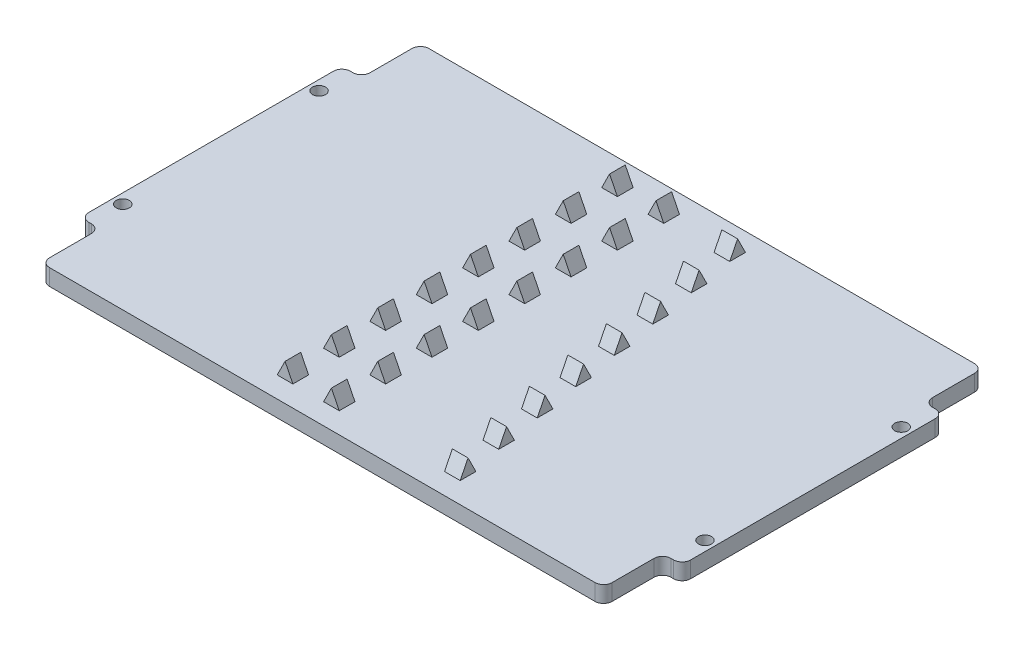
SolidWorks part; units mm, degrees
ref_plane "Front Plane" through (0, 0, 0) normal (0, 0, 1) x (1, 0, 0)
ref_plane "Top Plane" through (0, 0, 0) normal (0, 1, 0) x (1, 0, 0)
ref_plane "Right Plane" through (0, 0, 0) normal (1, 0, 0) x (0, 0, -1)
sketch "Sketch1" plane through (0, 0, 0) normal (0, 1, 0) x (1, 0, 0)
  line L1 (-54.61, -36.83) -> (54.61, -36.83)
  line L2 (-54.61, -36.83) -> (-54.61, 36.83)
  line L3 (-54.61, 36.83) -> (54.61, 36.83)
  line L4 (54.61, -36.83) -> (54.61, 36.83)
  line L5 (-54.61, -36.83) -> (54.61, 36.83) construction
  line L6 (-54.61, 36.83) -> (54.61, -36.83) construction
  point P0 (0, 0)
  dimension "D1" = 109.22
  dimension "D2" = 73.66
extrude "Boss-Extrude1" add sketch "Sketch1" against normal blind 3.175
ref_plane "Plane1" through (0, 0, -31.75) normal (0, 0, 1) x (1, 0, 0)
sketch "Sketch2" plane through (0, 0, -31.75) normal (0, 0, 1) x (1, 0, 0)
  line L0 (-12.81, 0) -> (-11.286, 3.048)
  line L3 (-11.286, 0) -> (-12.81, 0)
  line L4 (-11.286, 3.048) -> (-11.286, 0) construction
  line L5 (-11.286, 3.048) -> (-9.762, 0)
  line L6 (-54.61, 0) -> (54.61, 0) construction
  line L7 (-9.762, 0) -> (-11.286, 0)
  point P5 (-12.048, 0)
  dimension "D1" = 1.524
  dimension "D2" = 3.048
  dimension "D3" = 12.048
extrude "Boss-Extrude3" add sketch "Sketch2" along normal mid plane 3.048
pattern_linear "LPattern1" count 2 spacing 9 along (1, 0, 0) count 8 spacing 9 along (0, 0, 1) of "Boss-Extrude3"
sketch "Sketch3" plane through (0, 0, 0) normal (0, 1, 0) x (1, 0, 0)
  line L0 (-54.61, 36.83) -> (-54.61, -36.83) construction
  line L1 (-54.61, 25.4) -> (-58.42, 25.4)
  line L2 (-54.61, 25.4) -> (-54.61, -25.4)
  line L3 (-54.61, -25.4) -> (-58.42, -25.4)
  line L4 (-58.42, 25.4) -> (-58.42, -25.4)
  line L5 (0, 0) -> (0, 36.83) construction
  line L6 (54.61, 36.83) -> (-54.61, 36.83) construction
  line L7 (58.42, 25.4) -> (58.42, -25.4)
  line L8 (54.61, -25.4) -> (58.42, -25.4)
  line L9 (54.61, 25.4) -> (54.61, -25.4)
  line L10 (54.61, 25.4) -> (58.42, 25.4)
  circle A0 centre (-56.515, 19.05) radius 1.27
  circle A1 centre (-56.515, -19.05) radius 1.27
  circle A2 centre (56.515, -19.05) radius 1.27
  circle A3 centre (56.515, 19.05) radius 1.27
  point P6 (-58.42, 0)
  point P11 (-56.515, 25.4)
  dimension "D3" = 2.54
  dimension "D1" = 3.81
  dimension "D2" = 50.8
  dimension "D4" = 19.05
  dimension "D5" = 2
extrude "Boss-Extrude2" add sketch "Sketch3" against normal blind 3.175
fillet "Fillet1" radius 1.651 12 edges at (54.61, -1.5875, -36.83) (54.61, -1.5875, -25.4) (58.42, -1.5875, -25.4) (58.42, -1.5875, 25.4) (54.61, -1.5875, 25.4) (54.61, -1.5875, 36.83) (-54.61, -1.5875, 36.83) (-54.61, -1.5875, 25.4) (-58.42, -1.5875, 25.4) (-58.42, -1.5875, -25.4) (-54.61, -1.5875, -25.4) (-54.61, -1.5875, -36.83)
sketch "Sketch4" plane through (0, 0, 0) normal (1, 0, 0) x (0, 0, -1)
  line L0 (30.226, 0) -> (33.274, 0)
  line L1 (-23.749, 0) -> (23.749, 0) construction
  line L2 (33.274, 0) -> (31.75, 3.048)
  line L3 (31.75, 3.048) -> (30.226, 0)
  line L4 (31.75, 3.048) -> (31.75, 0) construction
  line L5 (12.226, 3.048) -> (15.274, 3.048) construction
  line L6 (30.226, 0) -> (33.274, 0) construction
extrude "Boss-Extrude4" add sketch "Sketch4" along normal blind 3.048 from offset 9
sketch "Sketch5" plane through (0, 0, 0) normal (1, 0, 0) x (0, 0, -1)
  line L0 (21.226, 0) -> (24.274, 0)
  line L2 (24.274, 0) -> (22.75, 3.048)
  line L3 (22.75, 3.048) -> (21.226, 0)
  line L4 (22.75, 3.048) -> (22.75, 0) construction
  line L7 (21.226, 0) -> (24.274, 0) construction
extrude "Boss-Extrude5" add sketch "Sketch5" along normal blind 3.048 from offset 10.524
sketch "Sketch6" plane through (0, 0, 0) normal (1, 0, 0) x (0, 0, -1)
  line L0 (12.226, 0) -> (15.274, 0)
  line L1 (12.226, 0) -> (15.274, 0) construction
  line L2 (15.274, 0) -> (13.75, 3.048)
  line L3 (13.75, 3.048) -> (12.226, 0)
  line L4 (13.75, 3.048) -> (13.75, 0) construction
extrude "Boss-Extrude6" add sketch "Sketch6" along normal blind 3.048 from offset 12.048
sketch "Sketch7" plane through (0, 0, 0) normal (1, 0, 0) x (0, 0, -1)
  line L0 (3.226, 0) -> (6.274, 0)
  line L2 (6.274, 0) -> (4.75, 3.048)
  line L3 (4.75, 3.048) -> (3.226, 0)
  line L4 (4.75, 3.048) -> (4.75, 0) construction
  line L5 (3.226, 0) -> (6.274, 0) construction
extrude "Boss-Extrude7" add sketch "Sketch7" along normal blind 3.048 from offset 13.572
sketch "Sketch8" plane through (0, 0, 0) normal (1, 0, 0) x (0, 0, -1)
  line L0 (-5.774, 0) -> (-2.726, 0)
  line L1 (-5.774, 0) -> (-2.726, 0) construction
  line L2 (-2.726, 0) -> (-4.25, 3.048)
  line L3 (-4.25, 3.048) -> (-5.774, 0)
  line L4 (-4.25, 3.048) -> (-4.25, 0) construction
extrude "Boss-Extrude8" add sketch "Sketch8" along normal blind 3.048 from offset 15.096
sketch "Sketch9" plane through (0, 0, 0) normal (1, 0, 0) x (0, 0, -1)
  line L0 (-14.774, 0) -> (-11.726, 0)
  line L2 (-11.726, 0) -> (-13.25, 3.048)
  line L3 (-13.25, 3.048) -> (-14.774, 0)
  line L4 (-13.25, 3.048) -> (-13.25, 0) construction
  line L5 (-14.774, 0) -> (-11.726, 0) construction
extrude "Boss-Extrude9" add sketch "Sketch9" along normal blind 3.048 from offset 16.62
sketch "Sketch10" plane through (0, 0, 0) normal (1, 0, 0) x (0, 0, -1)
  line L0 (-23.774, 0) -> (-20.726, 0)
  line L1 (-23.774, 0) -> (-20.726, 0) construction
  line L2 (-20.726, 0) -> (-22.25, 3.048)
  line L3 (-22.25, 3.048) -> (-23.774, 0)
  line L4 (-22.25, 3.048) -> (-22.25, 0) construction
extrude "Boss-Extrude10" add sketch "Sketch10" along normal blind 3.048 from offset 18.144
sketch "Sketch11" plane through (0, 0, 0) normal (1, 0, 0) x (0, 0, -1)
  line L0 (-32.774, 0) -> (-29.726, 0)
  line L2 (-29.726, 0) -> (-31.25, 3.048)
  line L3 (-31.25, 3.048) -> (-32.774, 0)
  line L4 (-31.25, 3.048) -> (-31.25, 0) construction
  line L5 (-32.774, 0) -> (-29.726, 0) construction
extrude "Boss-Extrude11" add sketch "Sketch11" along normal blind 3.048 from offset 19.668
